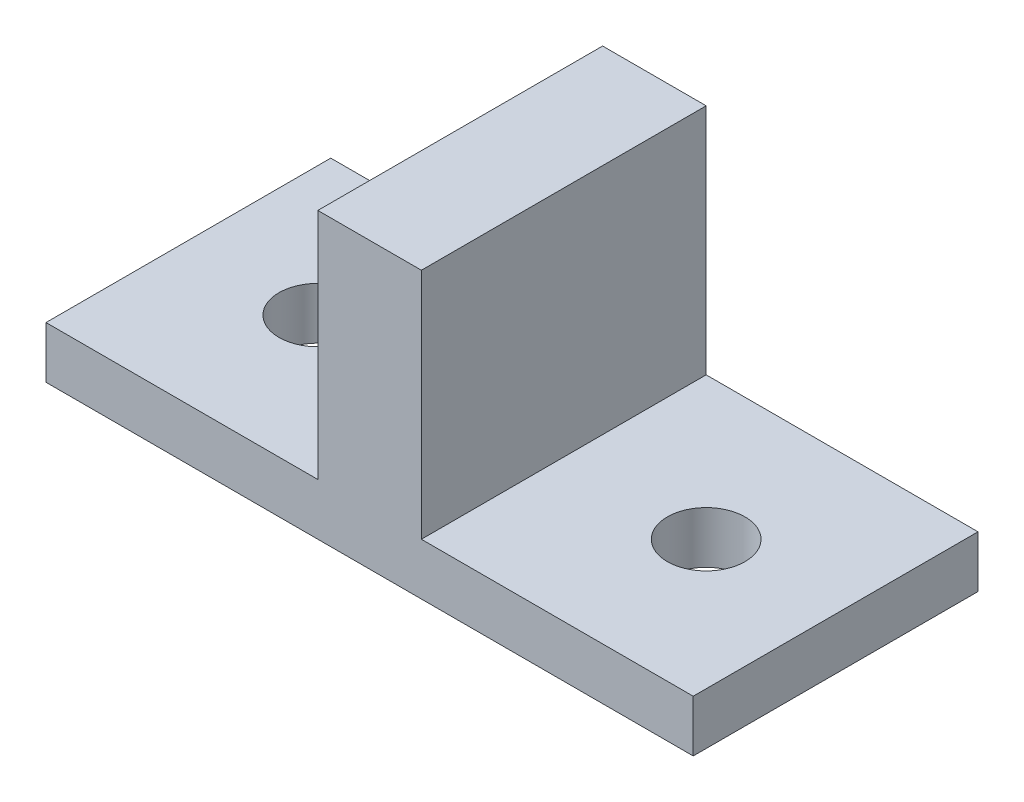
SolidWorks part; units mm, degrees
ref_plane "Front Plane" through (0, 0, 0) normal (0, 0, 1) x (1, 0, 0)
ref_plane "Top Plane" through (0, 0, 0) normal (0, 1, 0) x (1, 0, 0)
ref_plane "Right Plane" through (0, 0, 0) normal (1, 0, 0) x (0, 0, -1)
sketch "Sketch1" plane through (0, 0, 0) normal (0, 1, 0) x (1, 0, 0)
  line L1 (-62.5, 27.5) -> (62.5, 27.5)
  line L2 (-62.5, 27.5) -> (-62.5, -27.5)
  line L3 (-62.5, -27.5) -> (62.5, -27.5)
  line L4 (62.5, 27.5) -> (62.5, -27.5)
  line L5 (-62.5, 27.5) -> (62.5, -27.5) construction
  line L6 (-62.5, -27.5) -> (62.5, 27.5) construction
  point P0 (0, 0)
  dimension "D1" = 125
  dimension "D2" = 55
extrude "Boss-Extrude1" add sketch "Sketch1" along normal blind 10
sketch "Sketch2" plane through (0, 10, 0) normal (0, 1, 0) x (1, 0, 0)
  line L0 (0, 0) -> (0, -27.5)
  line L1 (-62.5, -27.5) -> (62.5, -27.5) construction
  line L2 (-37.5, -27.5) -> (37.5, -27.5)
  line L4 (30, 0) -> (0, 0) construction
  line L9 (50.9673, 0) -> (45, 0) construction
  circle A0 centre (-37.5, 0) radius 7.5
  circle A1 centre (37.5, 0) radius 7.5
  dimension "D2" = 15
  dimension "D1" = 37.5
extrude "Cut-Extrude1" cut sketch "Sketch2" against normal blind 10 contours A0 | A1
sketch "Sketch3" plane through (0, 10, 0) normal (0, 1, 0) x (1, 0, 0)
  line L0 (-10, -27.5) -> (10, -27.5)
  line L1 (-62.5, -27.5) -> (62.5, -27.5) construction
  line L2 (0, -15.9548) -> (0, -27.5) construction
  line L3 (-10, -27.5) -> (-10, 27.5)
  line L4 (62.5, 27.5) -> (-62.5, 27.5) construction
  line L5 (-10, 27.5) -> (10, 27.5)
  line L6 (10, 27.5) -> (10, -27.5)
  dimension "D1" = 10
extrude "Boss-Extrude2" add sketch "Sketch3" along normal blind 45
sketch "Sketch4" plane through (0, 55, 0) normal (0, 1, 0) x (1, 0, 0)
  line L0 (-10, -27.5) -> (10, -27.5)
  line L1 (-10, -27.5) -> (10, -27.5) construction
  line L2 (10, -27.5) -> (10, -12.5)
  line L3 (10, -27.5) -> (10, 27.5) construction
  line L4 (10, -12.5) -> (-10, -12.5)
  line L5 (-10, 27.5) -> (-10, -27.5) construction
  line L6 (-10, -12.5) -> (-10, -27.5)
  dimension "D1" = 15
